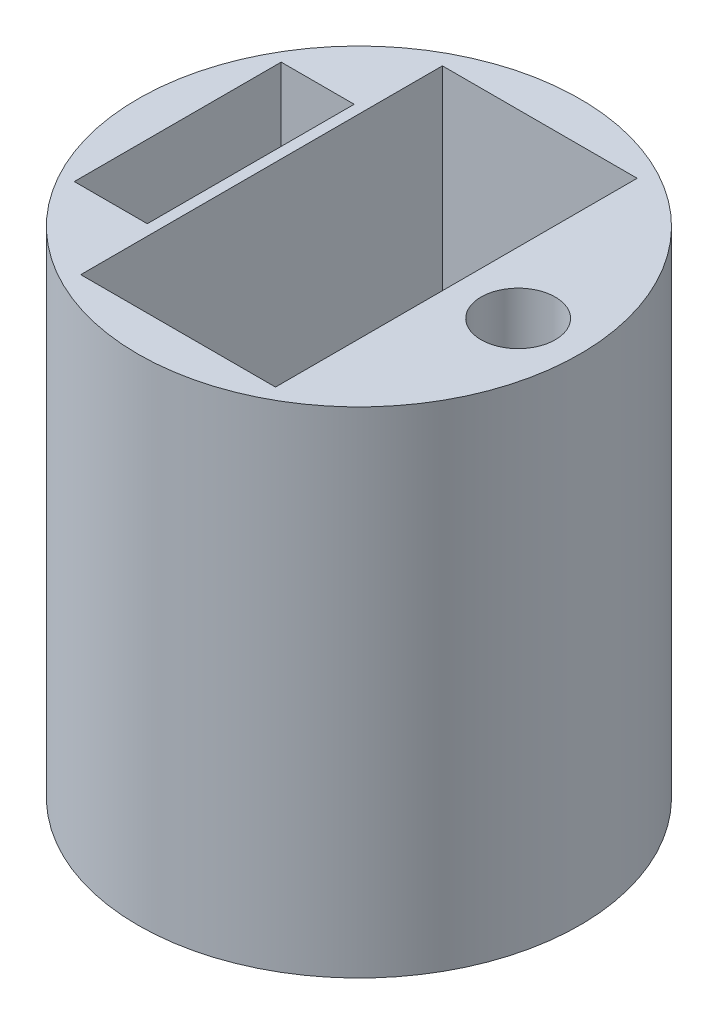
SolidWorks part; units mm, degrees
ref_plane "Front Plane" through (0, 0, 0) normal (0, 0, 1) x (1, 0, 0)
ref_plane "Top Plane" through (0, 0, 0) normal (0, 1, 0) x (1, 0, 0)
ref_plane "Right Plane" through (0, 0, 0) normal (1, 0, 0) x (0, 0, -1)
sketch "Sketch1" plane through (0, 0, 0) normal (0, 1, 0) x (1, 0, 0)
  circle A0 centre (0, 0) radius 90.805
  dimension "D1" = 181.61
extrude "Boss-Extrude1" add sketch "Sketch1" along normal blind 203.2
sketch "Sketch2" plane through (0, 203.2, 0) normal (0, 1, 0) x (1, 0, 0)
  line L1 (40.005, 74.295) -> (-40.005, 74.295)
  line L2 (40.005, 74.295) -> (40.005, -74.295)
  line L3 (40.005, -74.295) -> (-40.005, -74.295)
  line L4 (-40.005, 74.295) -> (-40.005, -74.295)
  line L5 (40.005, 74.295) -> (-40.005, -74.295) construction
  line L6 (40.005, -74.295) -> (-40.005, 74.295) construction
  point P0 (0, 0)
  dimension "D1" = 80.01
  dimension "D2" = 148.59
extrude "Cut-Extrude1" cut sketch "Sketch2" against normal blind 203.2
sketch "Sketch3" plane through (0, 203.2, 0) normal (0, 1, 0) x (1, 0, 0)
  line L0 (0, 0) -> (-44.45, 0) construction
  line L1 (-74.45, 42.5) -> (-44.45, 42.5)
  line L2 (-74.45, 42.5) -> (-74.45, -42.5)
  line L3 (-74.45, -42.5) -> (-44.45, -42.5)
  line L4 (-44.45, 42.5) -> (-44.45, -42.5)
  line L5 (0, 0) -> (0, 90.805) construction
  circle A0 centre (0, 0) radius 90.805 construction
  point P6 (-44.45, 0)
  dimension "D1" = 30
  dimension "D2" = 85
  dimension "D3" = 44.45
extrude "Cut-Extrude2" cut sketch "Sketch3" against normal blind 130
ref_plane "Plane1" through (0, 0, 0) normal (-1, 0, 0) x (0, 0, 1)
sketch "Sketch4" plane through (0, 203.2, 0) normal (0, 1, 0) x (1, 0, 0)
  line L0 (40.005, -74.295) -> (40.005, 74.295) construction
  circle A0 centre (65.405, 0) radius 15.24
  dimension "D1" = 30.48
  dimension "D2" = 25.4
extrude "Cut-Extrude3" cut sketch "Sketch4" against normal up to surface (203.2 mm away) up to face at (0, 0, 0)
sketch "Sketch5" plane through (0, 0, 0) normal (0, -1, 0) x (-1, 0, 0)
  circle A0 centre (53.34, -3.3939) radius 15.24
  dimension "D1" = 30.48
  dimension "D2" = 53.34
extrude "Cut-Extrude4" cut sketch "Sketch5" against normal blind 63.5
